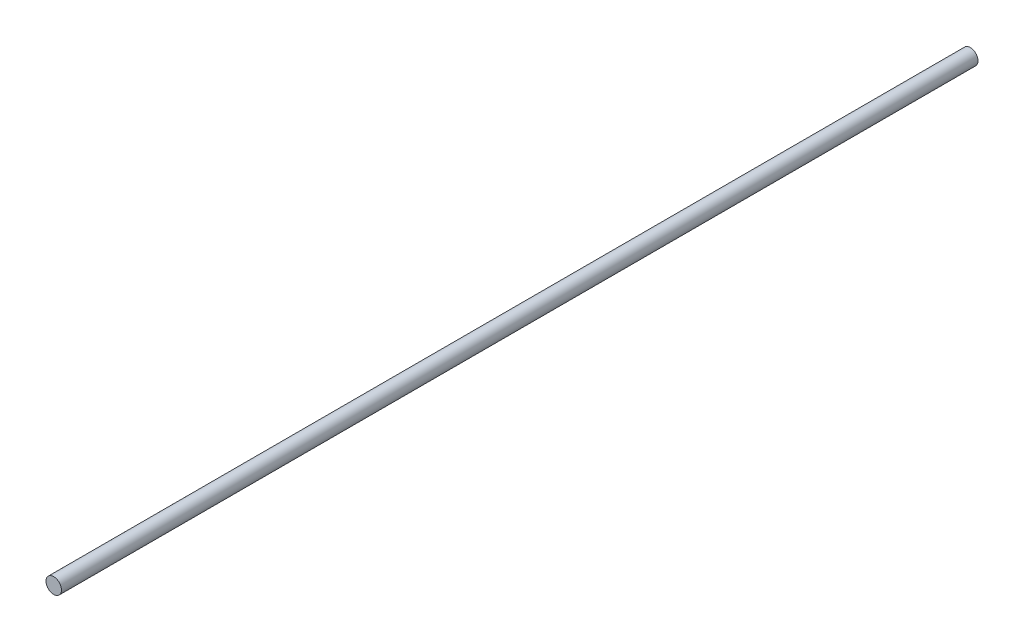
SolidWorks part; units mm, degrees
ref_plane "Alzado" through (0, 0, 0) normal (0, 0, 1) x (1, 0, 0)
ref_plane "Planta" through (0, 0, 0) normal (0, 1, 0) x (1, 0, 0)
ref_plane "Vista lateral" through (0, 0, 0) normal (1, 0, 0) x (0, 0, -1)
sketch "Croquis1" plane through (0, 0, 0) normal (0, 0, 1) x (1, 0, 0)
  circle A0 centre (0, 0) radius 3
  dimension "D1" = 6
extrude "Saliente-Extruir1" add sketch "Croquis1" along normal blind 356
